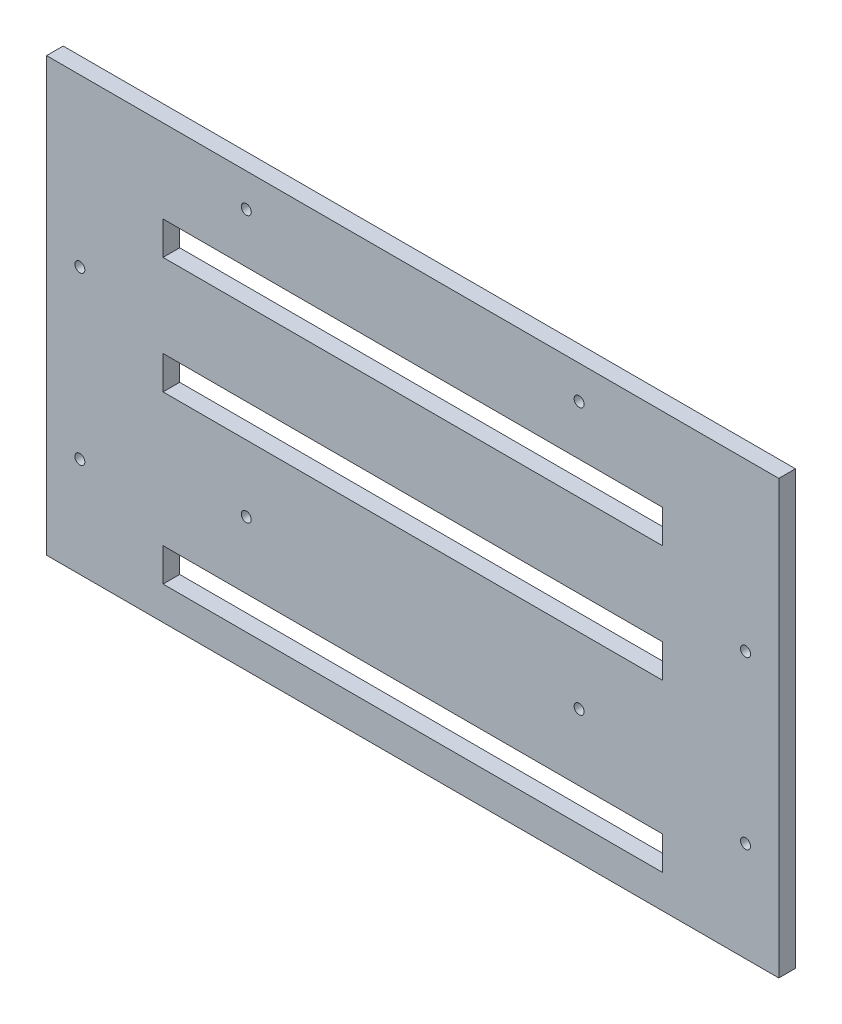
SolidWorks part; units mm, degrees
ref_plane "前视基准面" through (0, 0, 0) normal (0, 0, 1) x (1, 0, 0)
ref_plane "上视基准面" through (0, 0, 0) normal (0, 1, 0) x (1, 0, 0)
ref_plane "右视基准面" through (0, 0, 0) normal (1, 0, 0) x (0, 0, -1)
sketch "草图1" plane through (0, 0, 0) normal (0, 0, 1) x (1, 0, 0)
  line L1 (-110, 65) -> (110, 65)
  line L2 (-110, 65) -> (-110, -65)
  line L3 (-110, -65) -> (110, -65)
  line L4 (110, 65) -> (110, -65)
  line L5 (-110, 65) -> (110, -65) construction
  line L6 (-110, -65) -> (110, 65) construction
  point P0 (0, 0)
  dimension "D1" = 220
  dimension "D2" = 130
extrude "凸台-拉伸1" add sketch "草图1" along normal blind 5
sketch "草图2" plane through (0, 0, 5) normal (0, 0, 1) x (1, 0, 0)
  line L0 (-110, -65) -> (110, -65) construction
  line L1 (-50, 55) -> (50, 55) construction
  line L2 (-50, 55) -> (-50, -25) construction
  line L3 (-50, -25) -> (50, -25) construction
  line L4 (50, 55) -> (50, -25) construction
  line L5 (-50, 55) -> (50, -25) construction
  line L6 (-50, -25) -> (50, 55) construction
  circle A0 centre (-50, 55) radius 1.5
  circle A1 centre (50, 55) radius 1.5
  circle A2 centre (50, -25) radius 1.5
  circle A3 centre (-50, -25) radius 1.5
  point P0 (0, 15)
  point P10 (0, 0)
  dimension "D3" = 3
  dimension "D4" = 3
  dimension "D5" = 3
  dimension "D6" = 3
  dimension "D1" = 100
  dimension "D2" = 80
  dimension "D7" = 80
extrude "切除-拉伸1" cut sketch "草图2" against normal blind 5
sketch "草图3" plane through (0, 0, 5) normal (0, 0, 1) x (1, 0, 0)
  line L0 (110, -65) -> (110, 65) construction
  line L1 (-110, 65) -> (-110, -65) construction
  line L2 (100, 15) -> (100, -35) construction
  line L3 (110, 65) -> (-110, 65) construction
  circle A0 centre (100, 15) radius 1.5
  circle A1 centre (100, -35) radius 1.5
  circle A2 centre (-100, 15) radius 1.5
  circle A3 centre (-100, -35) radius 1.5
  dimension "D1" = 3
  dimension "D2" = 3
  dimension "D3" = 3
  dimension "D4" = 3
  dimension "D5" = 10
  dimension "D6" = 10
  dimension "D7" = 50
  dimension "D8" = 50
extrude "切除-拉伸2" cut sketch "草图3" against normal blind 5
sketch "草图4" plane through (0, 0, 5) normal (0, 0, 1) x (1, 0, 0)
  line L7 (-75, 5) -> (75, 5)
  line L8 (-75, 5) -> (-75, -5)
  line L9 (-75, -5) -> (75, -5)
  line L10 (75, 5) -> (75, -5)
  line L11 (-75, 5) -> (75, -5) construction
  line L12 (-75, -5) -> (75, 5) construction
  line L19 (-75, 40) -> (75, 40)
  line L20 (-75, 40) -> (-75, 30)
  line L21 (-75, 30) -> (75, 30)
  line L22 (75, 40) -> (75, 30)
  line L23 (-75, 40) -> (75, 30) construction
  line L24 (-75, 30) -> (75, 40) construction
  line L25 (-75, -45) -> (75, -45)
  line L26 (-75, -45) -> (-75, -55)
  line L27 (-75, -55) -> (75, -55)
  line L28 (75, -45) -> (75, -55)
  line L29 (-75, -45) -> (75, -55) construction
  line L30 (-75, -55) -> (75, -45) construction
  point P0 (0, 25)
  point P5 (0, 0)
  point P11 (0, -25)
  point P16 (0, -50)
  point P18 (0, 35)
  point P26 (244.9584, -72.1091)
  dimension "D1" = 10
  dimension "D3" = 150
  dimension "D6" = 25
  dimension "D9" = 10
  dimension "D10" = 10
  dimension "D11" = 150
  dimension "D12" = 10
  dimension "D14" = 150
extrude "切除-拉伸3" cut sketch "草图4" against normal blind 10
